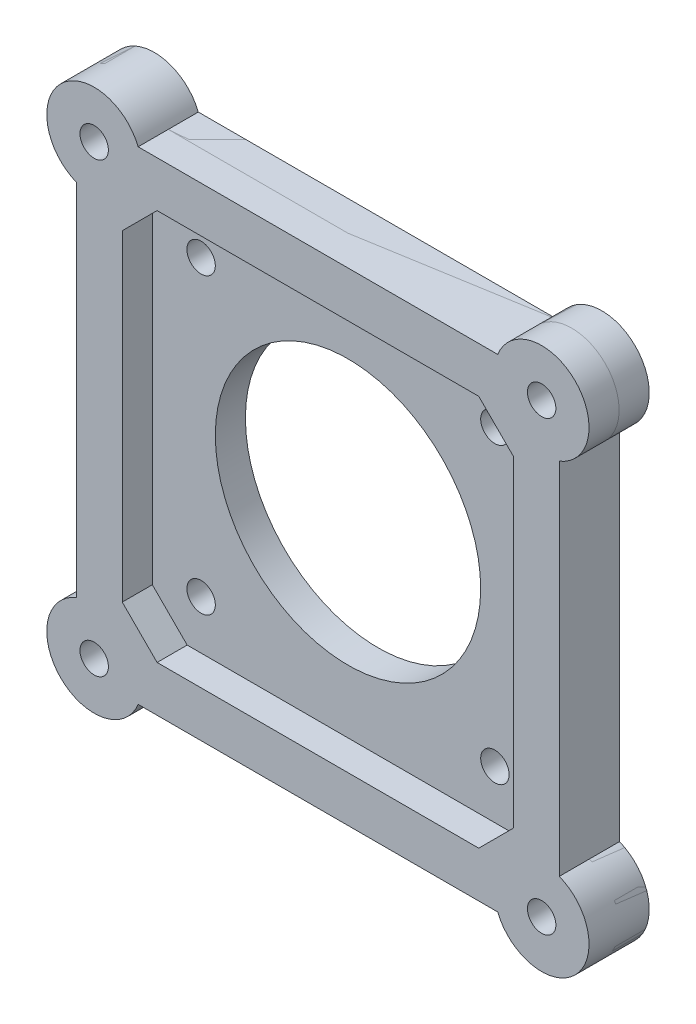
SolidWorks part; units mm, degrees
ref_plane "Plan de face" through (0, 0, 0) normal (0, 0, 1) x (1, 0, 0)
ref_plane "Plan de dessus" through (0, 0, 0) normal (0, 1, 0) x (1, 0, 0)
ref_plane "Plan de droite" through (0, 0, 0) normal (1, 0, 0) x (0, 0, -1)
sketch "Esquisse28" plane through (0, 0, 0) normal (0, 0, 1) x (1, 0, 0)
  line L0 (-18.97, -25.4754) -> (-25.4754, -18.97)
  line L1 (18.97, -25.4754) -> (-18.97, -25.4754)
  line L4 (25.4754, -18.97) -> (18.97, -25.4754)
  line L5 (25.4754, 18.97) -> (25.4754, -18.97)
  line L8 (18.97, 25.4754) -> (25.4754, 18.97)
  line L9 (-18.97, 25.4754) -> (18.97, 25.4754)
  line L10 (-25.4754, 18.97) -> (-18.97, 25.4754)
  line L11 (-25.4754, -18.97) -> (-25.4754, 18.97)
  line L16 (-16.97, -20.6455) -> (-20.6455, -16.97)
  line L17 (16.97, -20.6455) -> (-16.97, -20.6455)
  line L18 (20.6455, -16.97) -> (16.97, -20.6455)
  line L19 (20.6455, 16.97) -> (20.6455, -16.97)
  line L20 (16.97, 20.6455) -> (20.6455, 16.97)
  line L21 (-16.97, 20.6455) -> (16.97, 20.6455)
  line L22 (-20.6455, 16.97) -> (-16.97, 20.6455)
  line L23 (-20.6455, -16.97) -> (-20.6455, 16.97)
  point P0 (20.6455, -28.9519)
  point P1 (0, -20.6455)
  point P2 (0, -25.4754)
  point P3 (25.4754, 0)
  point P6 (0, 0)
  point P24 (20.6455, 0)
  dimension "D1" = 33.94
  dimension "D2" = 5.198
  dimension "D3" = 135
  dimension "D4" = 135
  dimension "D5" = 37.94
  dimension "D6" = 9.2
  dimension "D7" = 135
  dimension "D8" = 135
extrude "Boss.-Extru.2" add sketch "Esquisse28" along normal blind 6.35
sketch "Esquisse29" plane through (0, 0, 0) normal (0, 0, 1) x (1, 0, 0)
  line L0 (-46.0327, -46.0327) -> (46.0327, 46.0327) construction
  line L1 (-59.4617, 0) -> (59.4617, 0) construction
  circle A0 centre (23.6083, 23.6083) radius 5
  point P4 (0, 0)
  point P8 (0, 0)
  point P9 (32.5174, 23.4283)
  point P10 (25.891, 25.891)
  dimension "D2" = 10
  dimension "D1" = 45
extrude "Boss.-Extru.3" add sketch "Esquisse29" along normal up to surface (6.35 mm away) up to face at (0, 0, 6.35)
mirror "Symétrie1" about plane through (0, 0, 0) normal (1, 0, 0) of "Boss.-Extru.3"
mirror "Symétrie2" about plane through (0, 0, 0) normal (0, 1, 0) of "Symétrie1", "Boss.-Extru.3"
sketch "Esquisse30" plane through (0, 0, 6.35) normal (0, 0, 1) x (1, 0, 0)
  circle A0 centre (-23.6083, 23.6083) radius 1.5
  circle A1 centre (23.6083, 23.6083) radius 1.5
  circle A2 centre (23.6083, -23.6083) radius 1.5
  circle A3 centre (-23.6083, -23.6083) radius 1.5
  arc A4 (-25.4754, -18.97) -> (-18.97, -25.4754) centre (-23.6083, -23.6083) ccw construction
  arc A5 (-18.97, 25.4754) -> (-25.4754, 18.97) centre (-23.6083, 23.6083) ccw construction
  arc A6 (25.4754, 18.97) -> (18.97, 25.4754) centre (23.6083, 23.6083) ccw construction
  arc A7 (18.97, -25.4754) -> (25.4754, -18.97) centre (23.6083, -23.6083) ccw construction
  dimension "D1" = 3
extrude "Enlèv. mat.-Extru.1" cut sketch "Esquisse30" against normal through all
sketch "Esquisse31" plane through (0, 0, 0) normal (0, 0, 1) x (1, 0, 0)
  line L0 (-18.97, -25.4754) -> (18.97, -25.4754) construction
  line L1 (25.4754, -18.97) -> (25.4754, 18.97) construction
  line L2 (18.97, 25.4754) -> (-18.97, 25.4754) construction
  line L3 (-25.4754, 18.97) -> (-25.4754, -18.97) construction
  line L4 (-18.97, -25.4754) -> (18.97, -25.4754)
  line L5 (25.4754, -18.97) -> (25.4754, 18.97)
  line L6 (18.97, 25.4754) -> (-18.97, 25.4754)
  line L7 (-25.4754, 18.97) -> (-25.4754, -18.97)
  circle A0 centre (23.6083, 23.6083) radius 1.5 construction
  circle A1 centre (-23.6083, 23.6083) radius 1.5 construction
  circle A2 centre (-23.6083, -23.6083) radius 1.5 construction
  circle A3 centre (23.6083, -23.6083) radius 1.5 construction
  arc A4 (-25.4754, -18.97) -> (-18.97, -25.4754) centre (-23.6083, -23.6083) ccw construction
  arc A5 (18.97, -25.4754) -> (25.4754, -18.97) centre (23.6083, -23.6083) ccw construction
  arc A6 (25.4754, 18.97) -> (18.97, 25.4754) centre (23.6083, 23.6083) ccw construction
  arc A7 (-18.97, 25.4754) -> (-25.4754, 18.97) centre (-23.6083, 23.6083) ccw construction
  circle A8 centre (23.6083, 23.6083) radius 1.5
  circle A9 centre (-23.6083, 23.6083) radius 1.5
  circle A10 centre (-23.6083, -23.6083) radius 1.5
  circle A11 centre (23.6083, -23.6083) radius 1.5
  arc A12 (-25.4754, -18.97) -> (-18.97, -25.4754) centre (-23.6083, -23.6083) ccw
  arc A13 (18.97, -25.4754) -> (25.4754, -18.97) centre (23.6083, -23.6083) ccw
  arc A14 (25.4754, 18.97) -> (18.97, 25.4754) centre (23.6083, 23.6083) ccw
  arc A15 (-18.97, 25.4754) -> (-25.4754, 18.97) centre (-23.6083, 23.6083) ccw
extrude "Boss.-Extru.4" add sketch "Esquisse31" along normal blind 3.175 separate body
sketch "Esquisse32" plane through (0, 0, 3.175) normal (0, 0, 1) x (1, 0, 0)
  circle A0 centre (-15.5, -15.5) radius 1.5
  circle A1 centre (15.5, -15.5) radius 1.5
  circle A2 centre (15.5, 15.5) radius 1.5
  circle A3 centre (-15.5, 15.5) radius 1.5
  circle A4 centre (0, 0) radius 14
  dimension "D1" = 3
  dimension "D6" = 28
  dimension "D2" = 15.5
  dimension "D3" = 15.5
  dimension "D4" = 15.5
  dimension "D5" = 15.5
extrude "Enlèv. mat.-Extru.2" cut sketch "Esquisse32" against normal through all
